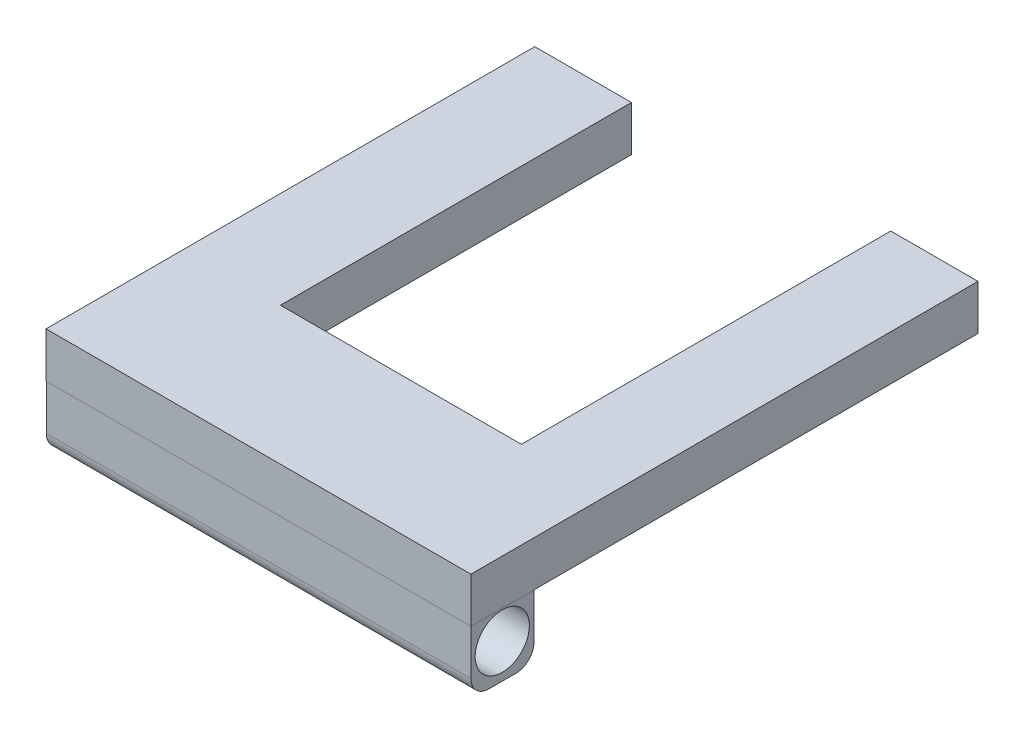
SolidWorks part; units mm, degrees
ref_plane "Front Plane" through (0, 0, 0) normal (0, 0, 1) x (1, 0, 0)
ref_plane "Top Plane" through (0, 0, 0) normal (0, 1, 0) x (1, 0, 0)
ref_plane "Right Plane" through (0, 0, 0) normal (1, 0, 0) x (0, 0, -1)
sketch "Sketch1" plane through (0, 0, 0) normal (0, 1, 0) x (1, 0, 0)
  line L0 (0, 0) -> (0, -54.102)
  line L1 (0, -54.102) -> (47.0297, -54.102)
  line L2 (47.0297, -54.102) -> (47.0297, 2.032)
  line L3 (47.0297, 2.032) -> (37.3777, 2.032)
  line L4 (37.3777, 2.032) -> (37.3777, -38.862)
  line L5 (37.3777, -38.862) -> (10.7077, -38.862)
  line L6 (10.7077, -38.862) -> (10.7077, 0)
  line L7 (10.7077, 0) -> (0, 0)
extrude "Boss-Extrude1" add sketch "Sketch1" along normal blind 5
sketch "Sketch2" plane through (47.0297, 0, 0) normal (1, 0, 0) x (0, 0, -1)
  line L1 (-54.102, 0) -> (2.032, 0) construction
  line L2 (-54.102, 0) -> (-47.102, 0)
  line L3 (-54.102, 0) -> (-54.102, -7)
  line L4 (-54.102, -7) -> (-47.102, -7)
  line L5 (-47.102, 0) -> (-47.102, -7)
  dimension "D1" = 7
  dimension "D2" = 7
extrude "Boss-Extrude2" add sketch "Sketch2" against normal blind 47 separate body
sketch "Sketch5" plane through (47.0297, 0, 0) normal (1, 0, 0) x (0, 0, -1)
  circle A0 centre (-50.6263, -3.1549) radius 3
  dimension "D1" = 6
extrude "Cut-Extrude1" cut sketch "Sketch5" against normal up to next (47 mm away)
fillet "Fillet2" radius 2 2 edges at (23.5297, -7, 47.102) (23.5297, -7, 54.102)
